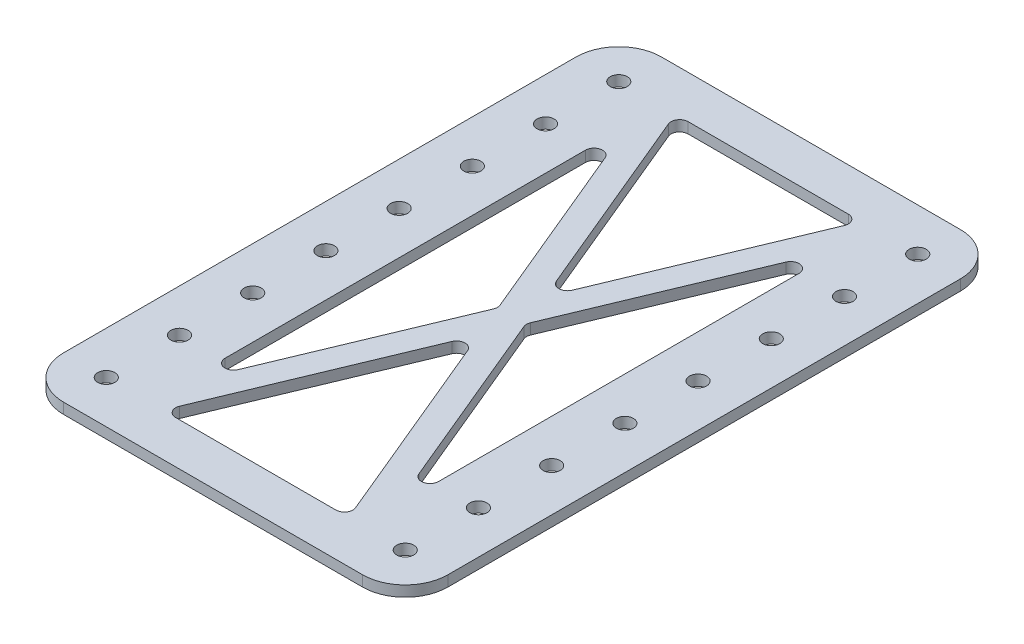
SolidWorks part; units mm, degrees
ref_plane "Front Plane" through (0, 0, 0) normal (0, 0, 1) x (1, 0, 0)
ref_plane "Top Plane" through (0, 0, 0) normal (0, 1, 0) x (1, 0, 0)
ref_plane "Right Plane" through (0, 0, 0) normal (1, 0, 0) x (0, 0, -1)
sketch "Sketch1" plane through (0, 0, 0) normal (0, 1, 0) x (1, 0, 0)
  line L1 (-57.15, -88.9) -> (57.15, -88.9)
  line L2 (-57.15, -88.9) -> (-57.15, 88.9)
  line L3 (-57.15, 88.9) -> (57.15, 88.9)
  line L4 (57.15, -88.9) -> (57.15, 88.9)
  line L5 (-57.15, -88.9) -> (57.15, 88.9) construction
  line L6 (-57.15, 88.9) -> (57.15, -88.9) construction
  point P0 (0, 0)
  dimension "D1" = 114.3
  dimension "D2" = 177.8
extrude "Boss-Extrude1" add sketch "Sketch1" along normal blind 3.175
sketch "Sketch2" plane through (0, 3.175, 0) normal (0, 1, 0) x (1, 0, 0)
  line L0 (57.15, 88.9) -> (-57.15, 88.9) construction
  line L1 (-57.15, 88.9) -> (-57.15, -88.9) construction
  line L2 (-57.15, -88.9) -> (57.15, -88.9) construction
  line L3 (0, 0) -> (0, 28.6343) construction
  circle A0 centre (-44.45, 76.2) radius 2.54
  circle A1 centre (-44.45, 54.4286) radius 2.54
  circle A2 centre (-44.45, 32.6571) radius 2.54
  circle A3 centre (-44.45, 10.8857) radius 2.54
  circle A4 centre (-44.45, -10.8857) radius 2.54
  circle A5 centre (-44.45, -32.6571) radius 2.54
  circle A6 centre (-44.45, -54.4286) radius 2.54
  circle A7 centre (-44.45, -76.2) radius 2.54
  circle A8 centre (44.45, -76.2) radius 2.54
  circle A9 centre (44.45, -54.4286) radius 2.54
  circle A10 centre (44.45, -32.6571) radius 2.54
  circle A11 centre (44.45, -10.8857) radius 2.54
  circle A12 centre (44.45, 10.8857) radius 2.54
  circle A13 centre (44.45, 32.6571) radius 2.54
  circle A14 centre (44.45, 54.4286) radius 2.54
  circle A15 centre (44.45, 76.2) radius 2.54
  dimension "D1" = 5.08
  dimension "D2" = 12.7
  dimension "D3" = 12.7
  dimension "D4" = 8
  dimension "D5" = 12.7
extrude "Cut-Extrude1" cut sketch "Sketch2" against normal blind 3.175
fillet "Fillet1" radius 12.7 4 edges at (-57.15, 1.5875, -88.9) (57.15, 1.5875, -88.9) (57.15, 1.5875, 88.9) (-57.15, 1.5875, 88.9)
sketch "Sketch3" plane through (0, 3.175, 0) normal (0, 1, 0) x (1, 0, 0)
  line L0 (44.45, 88.9) -> (-44.45, 88.9) construction
  line L1 (27.6225, -76.2) -> (-27.6225, -76.2)
  line L2 (31.75, -66.294) -> (31.75, 66.294)
  line L3 (27.6225, 76.2) -> (-27.6225, 76.2)
  line L4 (-31.75, -66.294) -> (-31.75, 66.294)
  line L7 (4.1275, 0) -> (31.75, 66.294)
  line L8 (-57.15, 76.2) -> (-57.15, -76.2) construction
  line L9 (-27.6225, 76.2) -> (0, 9.906)
  line L10 (-31.75, 66.294) -> (-4.1275, 0)
  line L11 (27.6225, 76.2) -> (0, 9.906)
  line L12 (0, -9.906) -> (27.6225, -76.2)
  line L13 (-27.6225, -76.2) -> (0, -9.906)
  line L14 (4.1275, 0) -> (31.75, -66.294)
  line L15 (-4.1275, 0) -> (-31.75, -66.294)
  point P0 (0, 0)
  dimension "D1" = 12.7
  dimension "D2" = 25.4
extrude "Cut-Extrude2" cut sketch "Sketch3" against normal through all
fillet "Fillet2" radius 2.54 12 edges at (-27.6225, 1.5875, 76.2) (27.6225, 1.5875, 76.2) (31.75, 1.5875, 66.294) (31.75, 1.5875, -66.294) (-27.6225, 1.5875, -76.2) (27.6225, 1.5875, -76.2) (-31.75, 1.5875, -66.294) (-4.1275, 1.5875, 0) (-31.75, 1.5875, 66.294) (0, 1.5875, -9.906) (4.1275, 1.5875, 0) (0, 1.5875, 9.906)
